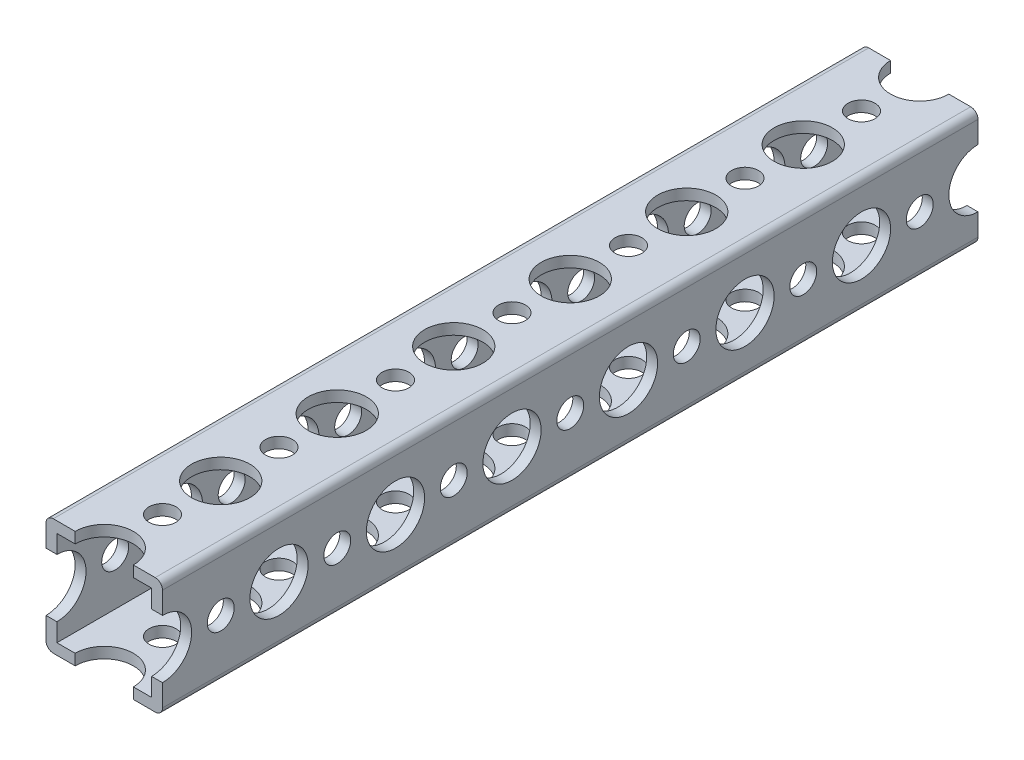
SolidWorks part; units mm, degrees
ref_plane "Front Plane" through (0, 0, 0) normal (0, 0, 1) x (1, 0, 0)
ref_plane "Top Plane" through (0, 0, 0) normal (0, 1, 0) x (1, 0, 0)
ref_plane "Right Plane" through (0, 0, 0) normal (1, 0, 0) x (0, 0, -1)
sketch "Sketch1" plane through (0, 0, 0) normal (0, 0, 1) x (1, 0, 0)
  line L1 (0, 0) -> (16, 0)
  line L2 (0, 0) -> (0, 16)
  line L3 (0, 16) -> (16, 16)
  line L4 (16, 0) -> (16, 16)
  dimension "D1" = 16
  dimension "D2" = 16
extrude "Extrude1" add sketch "Sketch1" against normal blind 112
sketch "Sketch2" plane through (0, 0, 0) normal (0, 0, 1) x (1, 0, 0)
  line L0 (-1.7793, 8) -> (18.8812, 8) construction
  line L1 (8, 16.9255) -> (8, -0.6999) construction
  line L3 (1.5, 14.5) -> (14.5, 14.5)
  line L4 (1.5, 14.5) -> (1.5, 1.5)
  line L5 (1.5, 1.5) -> (14.5, 1.5)
  line L6 (14.5, 14.5) -> (14.5, 1.5)
  line L7 (1.5, 14.5) -> (14.5, 1.5) construction
  line L8 (1.5, 1.5) -> (14.5, 14.5) construction
  point P4 (8, 8)
  dimension "D1" = 13
  dimension "D2" = 13
extrude "Extrude2" cut sketch "Sketch2" against normal through all
sketch "Sketch3" plane through (0, 16, 0) normal (0, 1, 0) x (1, 0, 0)
  line L0 (-10.6019, 48) -> (25.4979, 48) construction
  line L1 (8, -3.3001) -> (8, 305.034) construction
  line L2 (-10.6019, 80) -> (44.8988, 80) construction
  line L4 (16, 0) -> (0, 0) construction
  line L5 (-19.3069, 144) -> (85.0309, 144) construction
  circle A0 centre (8, 64) radius 4
  circle A1 centre (8, 32) radius 4
  circle A3 centre (8, 0) radius 4
  circle A4 centre (8, 96) radius 4
  circle A5 centre (8, 128) radius 4
  circle A6 centre (8, 160) radius 4
  circle A7 centre (8, 192) radius 4
  circle A8 centre (8, 224) radius 4
  circle A9 centre (8, 256) radius 4
  circle B0 centre (8, 48) radius 4
  circle B1 centre (8, 56) radius 1.85
  circle B2 centre (8, 40) radius 1.85
  circle B3 centre (8, 80) radius 4
  circle B4 centre (8, 88) radius 1.85
  circle B5 centre (8, 72) radius 1.85
  circle B6 centre (8, 16) radius 4
  circle B7 centre (8, 24) radius 1.85
  circle B8 centre (8, 8) radius 1.85
  circle B9 centre (8, 112) radius 4
  circle B10 centre (8, 120) radius 1.85
  circle B11 centre (8, 104) radius 1.85
  circle B12 centre (8, 144) radius 4
  circle B13 centre (8, 152) radius 1.85
  circle B14 centre (8, 136) radius 1.85
  circle B15 centre (8, 176) radius 4
  circle B16 centre (8, 184) radius 1.85
  circle B17 centre (8, 168) radius 1.85
  circle B18 centre (8, 208) radius 4
  circle B19 centre (8, 216) radius 1.85
  circle B20 centre (8, 200) radius 1.85
  circle B21 centre (8, 240) radius 4
  circle B22 centre (8, 248) radius 1.85
  circle B23 centre (8, 232) radius 1.85
  dimension "D1" = 24
  dimension "D2" = 16
  dimension "D4" = 16
  dimension "D5" = 32
  dimension "D7" = 16
  dimension "D13" = 48
  dimension "D3" = 24
  dimension "D6" = 64
  dimension "D8" = 48
  dimension "D9" = 32
  dimension "D10" = 64
  dimension "D11" = 96
  dimension "D14" = 16
  dimension "D15" = 80
  dimension "D16" = 112
sketch_block_instance "Block2-1"
sketch_block "Block2"
sketch_block_instance "Block2-4"
sketch_block_instance "Block2-6"
sketch_block_instance "Block2-11"
sketch_block_instance "Block2-12"
sketch_block_instance "Block2-17"
sketch_block_instance "Block2-18"
sketch_block_instance "Block2-19"
extrude "Extrude3" cut sketch "Sketch3" against normal through all
sketch "Sketch4" plane through (16, 0, 0) normal (1, 0, 0) x (0, 0, -1)
  line L0 (-4.9809, 8) -> (308.0277, 8) construction
  line L1 (48, 20.3919) -> (48, -4.2435) construction
  line L2 (0, 0) -> (0, 16) construction
  line L4 (80, -7.5844) -> (80, 23.8371) construction
  line L5 (144, 22.3836) -> (144, -28.3788) construction
  circle A0 centre (32, 8) radius 4
  circle A1 centre (64, 8) radius 4
  circle A2 centre (0, 8) radius 4
  circle A4 centre (96, 8) radius 4
  circle A5 centre (128, 8) radius 4
  circle A6 centre (160, 8) radius 4
  circle A7 centre (192, 8) radius 4
  circle A8 centre (224, 8) radius 4
  circle A9 centre (256, 8) radius 4
  circle B0 centre (48, 8.0742) radius 4
  circle B1 centre (40, 8.0742) radius 1.85
  circle B2 centre (56, 8.0742) radius 1.85
  circle B3 centre (80, 8) radius 4
  circle B4 centre (72, 8) radius 1.85
  circle B5 centre (88, 8) radius 1.85
  circle B6 centre (16, 8) radius 4
  circle B7 centre (8, 8) radius 1.85
  circle B8 centre (24, 8) radius 1.85
  circle B9 centre (112, 8) radius 4
  circle B10 centre (104, 8) radius 1.85
  circle B11 centre (120, 8) radius 1.85
  circle B12 centre (144, 8) radius 4
  circle B13 centre (136, 8) radius 1.85
  circle B14 centre (152, 8) radius 1.85
  circle B15 centre (176, 8) radius 4
  circle B16 centre (168, 8) radius 1.85
  circle B17 centre (184, 8) radius 1.85
  circle B18 centre (208, 8) radius 4
  circle B19 centre (200, 8) radius 1.85
  circle B20 centre (216, 8) radius 1.85
  circle B21 centre (240, 8) radius 4
  circle B22 centre (232, 8) radius 1.85
  circle B23 centre (248, 8) radius 1.85
  dimension "D3" = 16
  dimension "D5" = 32
  dimension "D7" = 16
  dimension "D13" = 16
  dimension "D1" = 24
  dimension "D2" = 24
  dimension "D4" = 16
  dimension "D6" = 64
  dimension "D8" = 48
  dimension "D9" = 32
  dimension "D10" = 64
  dimension "D11" = 96
  dimension "D14" = 48
  dimension "D15" = 80
  dimension "D16" = 112
sketch_block_instance "Block2-8"
sketch_block_instance "Block2-9"
sketch_block_instance "Block2-10"
sketch_block_instance "Block2-14"
sketch_block_instance "Block2-15"
sketch_block_instance "Block2-22"
sketch_block_instance "Block2-23"
sketch_block_instance "Block2-24"
extrude "Extrude4" cut sketch "Sketch4" against normal through all
fillet "Fillet1" radius 1 4 edges at (0, 0, -56) (16, 0, -56) (0, 16, -56) (16, 16, -56)
